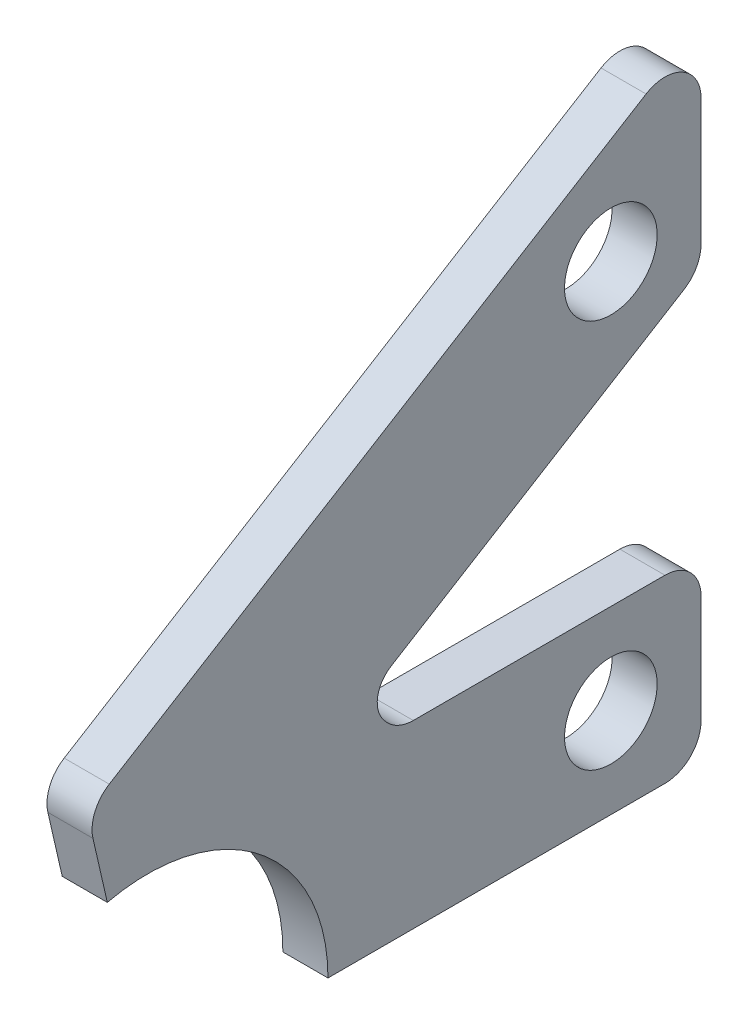
SolidWorks part; units mm, degrees
material "AISI 4130 Steel, annealed at 865C"
ref_plane "Front Plane" through (0, 0, 0) normal (0, 0, 1) x (1, 0, 0)
ref_plane "Top Plane" through (0, 0, 0) normal (0, 1, 0) x (1, 0, 0)
ref_plane "Right Plane" through (0, 0, 0) normal (1, 0, 0) x (0, 0, -1)
sketch "Sketch2" plane through (-112.555, 0, -573.5897) normal (-1, 0, 0) x (0, 0.6231, 0.7821)
  line L0 (845.7718, 136.9996) -> (864.3306, 122.2137)
  line L1 (871.0899, 172.8543) -> (811.2713, 97.7721) construction
  line L2 (864.3306, 122.2137) -> (884.1965, 122.2137) construction
  line L3 (884.1965, 122.2137) -> (887.7358, 125.0335)
  line L4 (853.6855, 146.9326) -> (867.5451, 135.8905)
  line L5 (888.541, 127.8859) -> (873.4237, 169.576)
  line L6 (871.3239, 138.1115) -> (863.0777, 160.8527)
  line L7 (845.3679, 140.569) -> (850.1161, 146.5287)
  line L8 (863.479, 163.3013) -> (869.0493, 170.2929)
  line L9 (852.7085, 139.592) -> (869.7744, 161.0125) construction
  circle A0 centre (874.2635, 114.3) radius 12.7 construction
  arc A1 (864.3306, 122.2137) -> (884.1965, 122.2137) centre (874.2635, 114.3) cw
  arc A2 (887.7358, 125.0335) -> (888.541, 127.8859) centre (886.1531, 127.0201) ccw
  circle A3 centre (852.7085, 139.592) radius 3.2639
  circle A4 centre (869.7744, 161.0125) radius 3.2639
  arc A6 (869.8308, 135.4301) -> (869.6684, 135.3953) centre (874.2635, 114.3) ccw
  arc A7 (845.7718, 136.9996) -> (845.3679, 140.569) centre (847.3545, 138.9862) cw
  arc A8 (853.6855, 146.9326) -> (850.1161, 146.5287) centre (852.1027, 144.946) ccw
  arc A9 (869.0493, 170.2929) -> (873.4237, 169.576) centre (871.0358, 168.7102) cw
  arc A10 (863.0777, 160.8527) -> (863.479, 163.3013) centre (865.4656, 161.7186) cw
  arc A11 (867.5451, 135.8905) -> (869.6684, 135.3953) centre (869.1278, 137.8771) ccw
  arc A12 (871.3239, 138.1115) -> (869.8308, 135.4301) centre (869.4136, 137.4188) cw
  point P17 (889.163, 126.1705)
  point P22 (0, 0)
  point P23 (0, 0)
  point P25 (843.7852, 138.5824)
  point P28 (851.6989, 148.5153)
  point P31 (871.8768, 173.842)
  point P34 (862.593, 162.1893)
  dimension "D5" = 2.54
  dimension "D6" = 6.5278
  dimension "D10" = 6.5278
  dimension "D9" = 2.54
  dimension "D4" = 8.89
  dimension "D12" = 2.54
  dimension "D13" = 2.54
  dimension "D14" = 2.54
  dimension "D15" = 2.54
  dimension "D16" = 2.032
  dimension "D1" = 12.7
  dimension "D2" = 12.7
  dimension "D3" = 6.35
  dimension "D7" = 6.35
  dimension "D8" = 6.35
  dimension "D11" = 6.35
extrude "Boss-Extrude1" add sketch "Sketch2" along normal blind 3.175 contours L4 A6 L6 L8 L5 A2 L3 A1 L0 L7
ref_plane "Plane1" through (0, 375.1306, -298.8699) normal (0, -0.7821, 0.6231) x (-1, 0, 0)
